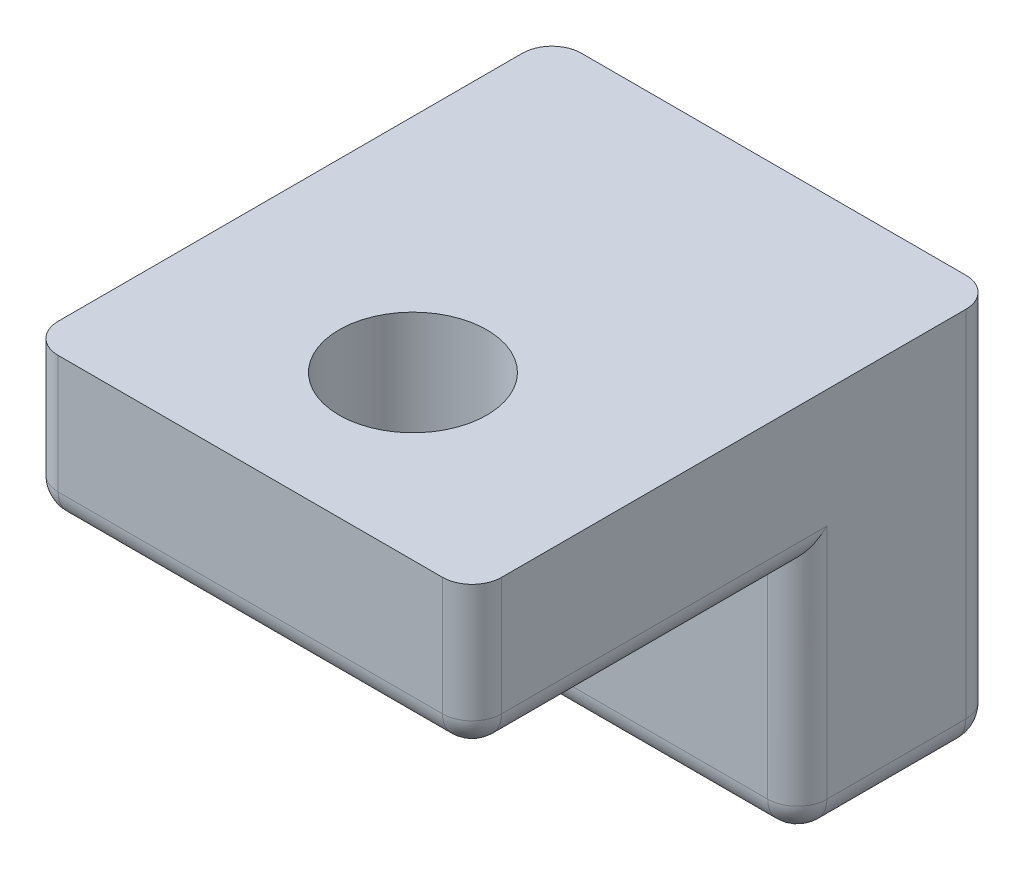
SolidWorks part; units mm, degrees
ref_plane "Front Plane" through (0, 0, 0) normal (0, 0, 1) x (1, 0, 0)
ref_plane "Top Plane" through (0, 0, 0) normal (0, 1, 0) x (1, 0, 0)
ref_plane "Right Plane" through (0, 0, 0) normal (1, 0, 0) x (0, 0, -1)
sketch "Sketch1" plane through (0, 0, 0) normal (1, 0, 0) x (0, 0, -1)
  line L0 (0, 0) -> (0, 8)
  line L1 (0, 8) -> (-11, 8)
  line L2 (-11, 8) -> (-11, 13)
  line L3 (-11, 13) -> (6.7, 13)
  line L4 (6.7, 13) -> (6.7, 0)
  line L5 (6.7, 0) -> (0, 0)
  point P3 (-5.5, 8)
  dimension "D1" = 6.7
  dimension "D2" = 12.2
  dimension "D3" = 8
  dimension "D4" = 5
extrude "Boss-Extrude1" add sketch "Sketch1" along normal mid plane 15
sketch "Sketch2" plane through (0, 13, 0) normal (0, 1, 0) x (1, 0, 0)
  line L0 (7.5, 0) -> (-7.5, 0) construction
  line L1 (7.5, 0) -> (-7.5, 0) construction
  line L2 (0, 0) -> (0, -11) construction
  line L3 (7.5, -11) -> (-7.5, -11) construction
  circle A0 centre (0, -5.5) radius 2.5
  dimension "D1" = 5
extrude "Cut-Extrude1" cut sketch "Sketch2" against normal up to next
fillet "Fillet1" radius 1 13 edges at (0, 0, 0) (7.5, 0, -3.35) (0, 0, -6.7) (-7.5, 0, -3.35) (0, 8, 11) (-7.5, 8, 5.5) (7.5, 8, 5.5) (7.5, 4, 0) (-7.5, 4, 0) (-7.5, 6.5, -6.7) (-7.5, 10.5, 11) (7.5, 10.5, 11) (7.5, 6.5, -6.7)
